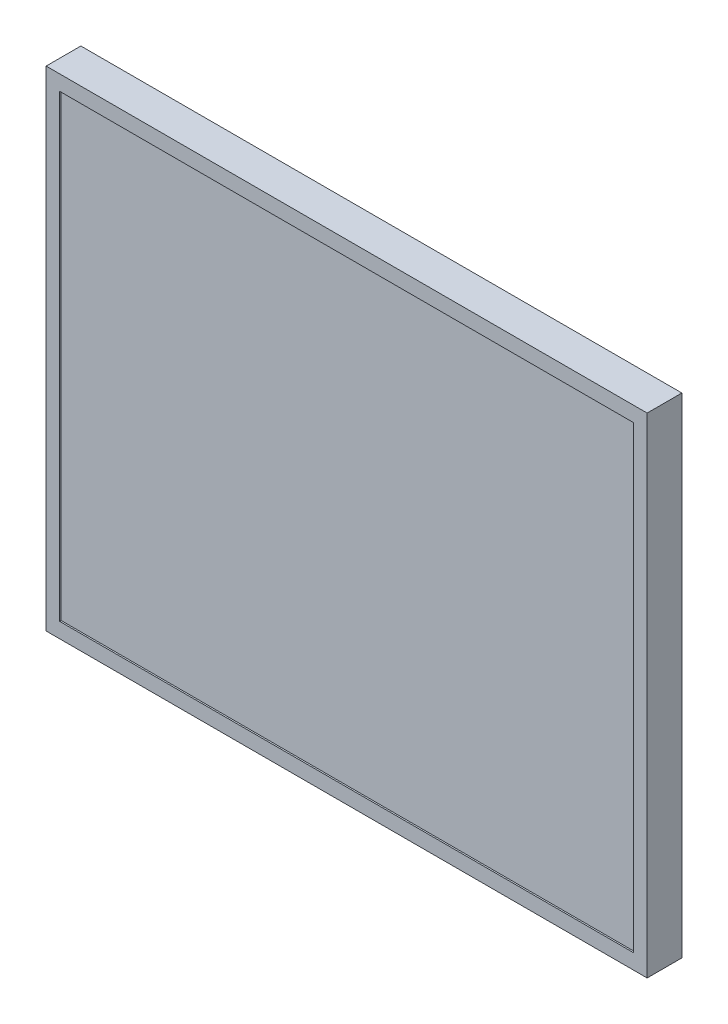
SolidWorks part; units mm, degrees
ref_plane "Front Plane" through (0, 0, 0) normal (0, 0, 1) x (1, 0, 0)
ref_plane "Top Plane" through (0, 0, 0) normal (0, 1, 0) x (1, 0, 0)
ref_plane "Right Plane" through (0, 0, 0) normal (1, 0, 0) x (0, 0, -1)
sketch "Sketch1" plane through (0, 0, 0) normal (0, 0, 1) x (1, 0, 0)
  line L1 (0, 0) -> (398, 0)
  line L2 (0, 0) -> (0, 324)
  line L3 (0, 324) -> (398, 324)
  line L4 (398, 0) -> (398, 324)
  dimension "D1" = 398
  dimension "D2" = 324
extrude "Boss-Extrude1" add sketch "Sketch1" along normal blind 23
sketch "Sketch2" plane through (0, 0, 23) normal (0, 0, 1) x (1, 0, 0)
  line L0 (0, 324) -> (0, 0) construction
  line L1 (9, 10) -> (389, 10)
  line L2 (9, 10) -> (9, 314)
  line L3 (9, 314) -> (389, 314)
  line L4 (389, 10) -> (389, 314)
  line L5 (0, 0) -> (398, 0) construction
  dimension "D1" = 304
  dimension "D2" = 380
  dimension "D3" = 9
  dimension "D4" = 10
extrude "Cut-Extrude1" cut sketch "Sketch2" against normal blind 1
sketch "Sketch3" plane through (0, 0, 0) normal (0, 0, -1) x (-1, 0, 0)
  line L0 (-398, 0) -> (-398, 324) construction
  line L1 (-374, 79) -> (-52, 79)
  line L2 (-374, 79) -> (-374, 241)
  line L3 (-374, 241) -> (-52, 241)
  line L4 (-52, 79) -> (-52, 241)
  line L5 (0, 324) -> (0, 0) construction
  line L6 (-398, 324) -> (0, 324) construction
  line L7 (0, 0) -> (-398, 0) construction
  dimension "D1" = 162
  dimension "D2" = 322
  dimension "D3" = 24
  dimension "D4" = 52
  dimension "D5" = 83
  dimension "D6" = 79
extrude "Boss-Extrude2" add sketch "Sketch3" along normal blind 30
chamfer "Chamfer1" distance 20 distance2 30 1 edges at (374, 160, -30)
sketch "Sketch4" plane through (0, 79, 0) normal (0, -1, 0) x (1, 0, 0)
  line L0 (374, -10) -> (374, 0) construction
  line L1 (54, -20) -> (84, -20)
  line L2 (54, -20) -> (54, -10)
  line L3 (54, -10) -> (84, -10)
  line L4 (84, -20) -> (84, -10)
  line L5 (99, -20) -> (134, -20)
  line L6 (99, -20) -> (99, -10)
  line L7 (99, -10) -> (134, -10)
  line L8 (134, -20) -> (134, -10)
  line L9 (319, -28) -> (289, -28)
  line L10 (319, -28) -> (319, -2)
  line L11 (319, -2) -> (289, -2)
  line L12 (289, -28) -> (289, -2)
  line L13 (344, -30) -> (52, -30) construction
  line L14 (374, 0) -> (52, 0) construction
  point P14 (374, -5)
  dimension "D1" = 55
  dimension "D2" = 85
  dimension "D3" = 240
  dimension "D4" = 275
  dimension "D5" = 290
  dimension "D6" = 320
  dimension "D7" = 2
  dimension "D8" = 2
  dimension "D9" = 10
  dimension "D10" = 10
  dimension "D11" = 10
  dimension "D12" = 10
extrude "Boss-Extrude3" add sketch "Sketch4" along normal blind 10
sketch "Sketch5" plane through (0, 0, -30) normal (0, 0, -1) x (-1, 0, 0)
  line L0 (-52, 79) -> (-52, 241) construction
  line L1 (-52, 106) -> (-67, 106)
  line L2 (-52, 106) -> (-52, 135)
  line L3 (-52, 135) -> (-67, 135)
  line L4 (-67, 106) -> (-67, 135)
  line L5 (-344, 79) -> (-52, 79) construction
  dimension "D1" = 27
  dimension "D2" = 56
  dimension "D3" = 15
extrude "Cut-Extrude2" cut sketch "Sketch5" against normal blind 25
